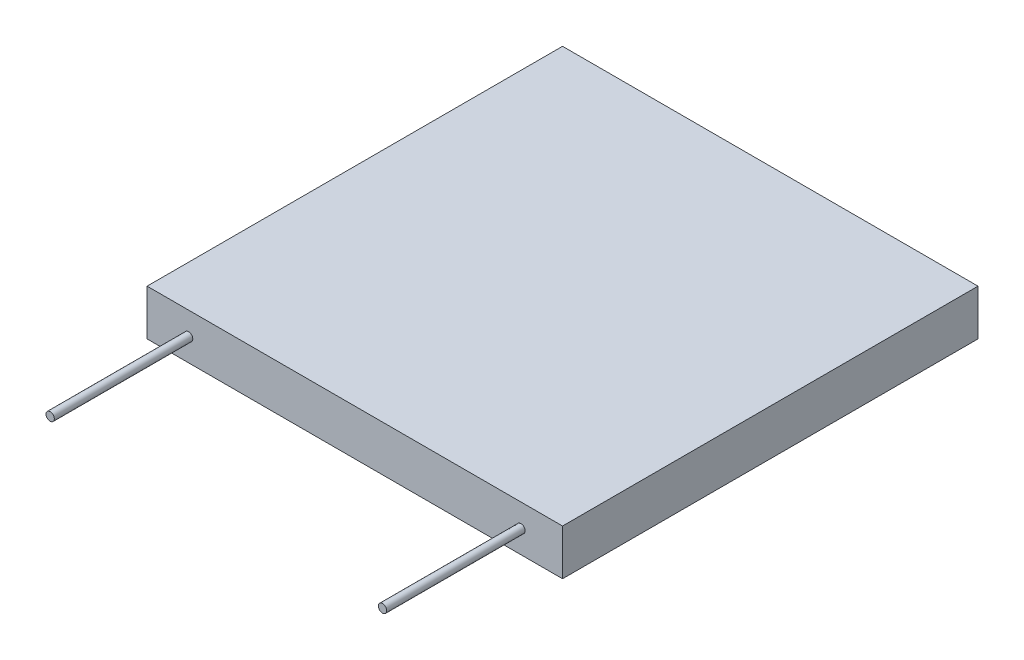
SolidWorks part; units mm, degrees
ref_plane "前视基准面" through (0, 0, 0) normal (0, 0, 1) x (1, 0, 0)
ref_plane "上视基准面" through (0, 0, 0) normal (0, 1, 0) x (1, 0, 0)
ref_plane "右视基准面" through (0, 0, 0) normal (1, 0, 0) x (0, 0, -1)
sketch "草图1" plane through (0, 0, 0) normal (0, 1, 0) x (1, 0, 0)
  line L0 (-59.7364, 0) -> (83.9948, 0) construction
  line L1 (-15, 15) -> (15, 15)
  line L2 (-15, 15) -> (-15, -15)
  line L3 (-15, -15) -> (15, -15)
  line L4 (15, 15) -> (15, -15)
  line L5 (0, 52.7621) -> (0, -60.9493) construction
  dimension "D1" = 30
  dimension "D2" = 30
extrude "拉伸1" add sketch "草图1" along normal blind 3.3
sketch "草图2" plane through (0, 0, 15) normal (0, 0, 1) x (1, 0, 0)
  line L0 (-9.3144, 1.65) -> (9.8458, 1.65) construction
  line L1 (-15, 3.3) -> (15, 3.3) construction
  line L2 (-15, 0) -> (15, 0) construction
  line L3 (0, 5.0008) -> (0, -4.2198) construction
  line L4 (-12, 3.3543) -> (-12, -1.6197) construction
  circle A0 centre (-12, 1.65) radius 0.3
  circle A1 centre (12, 1.65) radius 0.3
  dimension "D2" = 0.6
  dimension "D1" = 12
extrude "拉伸2" add sketch "草图2" along normal blind 10
